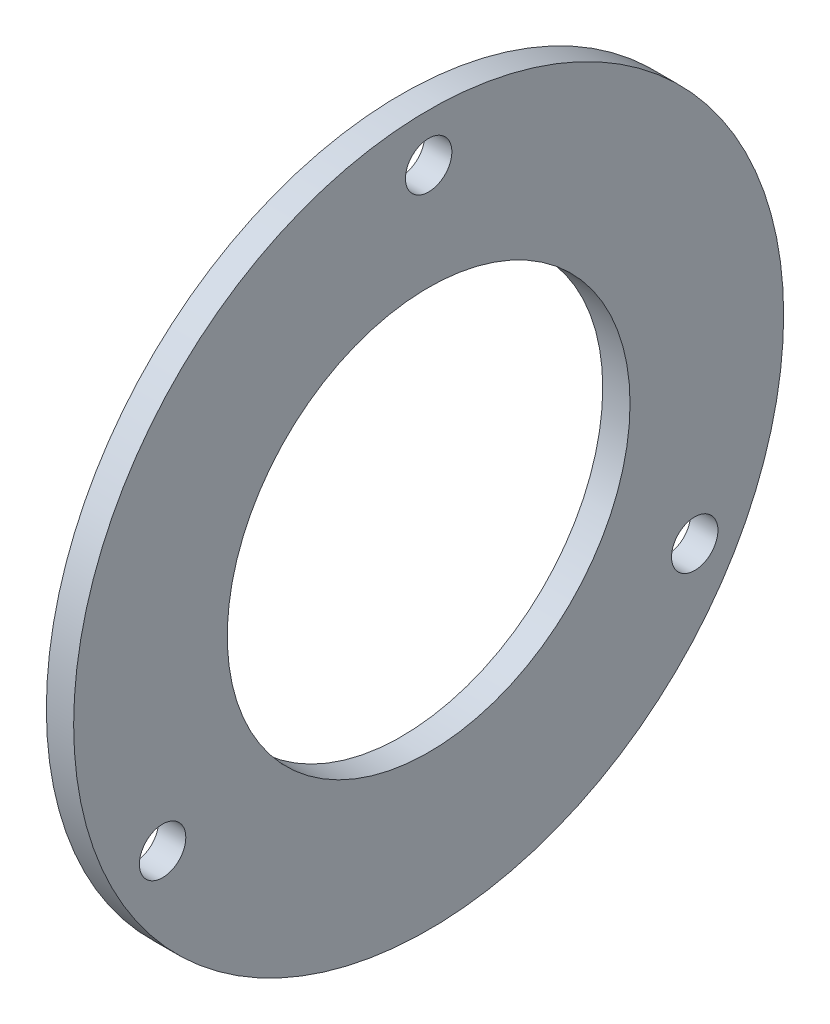
SolidWorks part; units mm, degrees
ref_plane "Front Plane" through (0, 0, 0) normal (1, 0, 0) x (0, 1, 0)
ref_plane "Top Plane" through (0, 0, 0) normal (0, 0, 1) x (0, 1, 0)
ref_plane "Right Plane" through (0, 0, 0) normal (0, 1, 0) x (-1, 0, 0)
sketch "Sketch1" plane through (0, 0, 0) normal (1, 0, 0) x (0, 1, 0)
  circle A0 centre (0, 0) radius 26
  dimension "D1" = 52
extrude "Boss-Extrude1" add sketch "Sketch1" along normal blind 2
sketch "Sketch2" plane through (2, 0, 0) normal (1, 0, 0) x (0, 1, 0)
  circle A0 centre (0, 0) radius 14.75
  dimension "D1" = 29.5
extrude "Cut-Extrude1" cut sketch "Sketch2" against normal through all
sketch "Sketch3" plane through (2, 0, 0) normal (1, 0, 0) x (0, 1, 0)
  line L0 (0, 0) -> (22.5, 0) construction
  line L1 (0, 0) -> (22.5, 0) construction
  line L2 (0, 0) -> (-11.25, -19.4856) construction
  circle A0 centre (22.5, 0) radius 1.7
  circle A1 centre (-11.25, -19.4856) radius 1.7
  circle A2 centre (-11.25, 19.4856) radius 1.7
  point P4 (0, 0)
  point P5 (0, 0)
  dimension "D2" = 3.4
  dimension "D1" = 22.5
  dimension "D4" = 120
  dimension "D3" = 3
extrude "Cut-Extrude2" cut sketch "Sketch3" against normal through all
